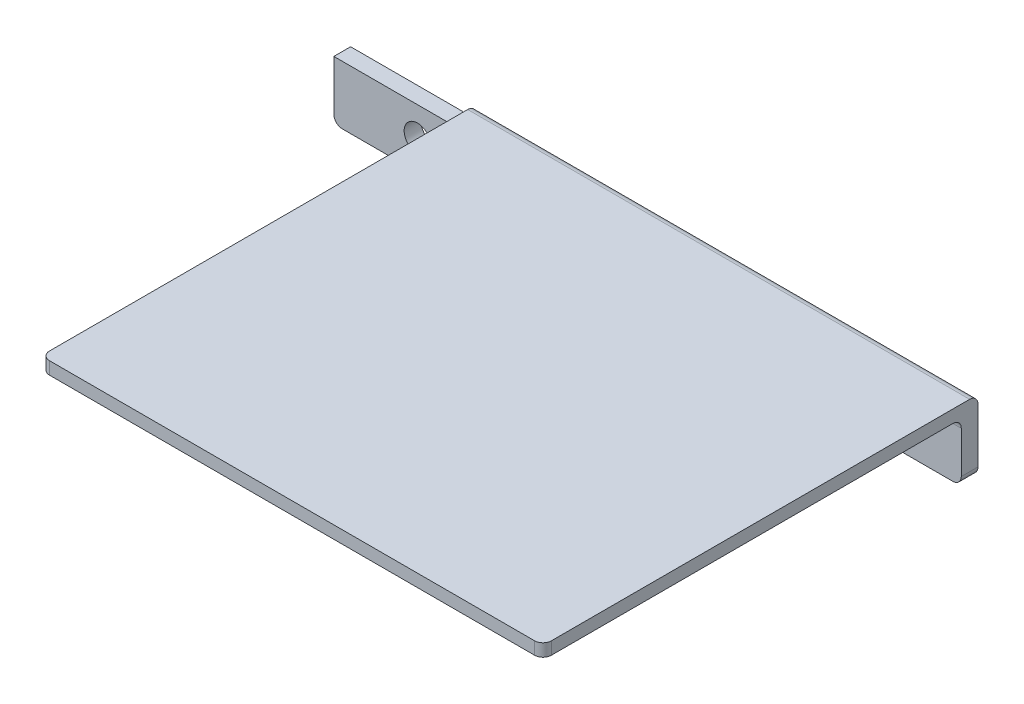
SolidWorks part; units mm, degrees
ref_plane "前视基准面" through (0, 0, 0) normal (0, 0, 1) x (1, 0, 0)
ref_plane "上视基准面" through (0, 0, 0) normal (0, 1, 0) x (1, 0, 0)
ref_plane "右视基准面" through (0, 0, 0) normal (1, 0, 0) x (0, 0, -1)
sketch "草图1" plane through (0, 0, 0) normal (0, 0, 1) x (1, 0, 0)
  line L1 (15, 0) -> (75, 0)
  line L2 (0, -1.5) -> (0, -8.5)
  line L3 (0, -8.5) -> (75, -8.5)
  line L4 (75, 0) -> (75, -8.5)
  line L7 (0, -1.5) -> (15, -1.5)
  line L8 (15, 0) -> (15, -1.5)
  circle A0 centre (10, -5) radius 1.6
  circle A1 centre (60, -5) radius 1.6
  dimension "D3" = 2
  dimension "D4" = 10
  dimension "D5" = 3.5
  dimension "D1" = 8.5
  dimension "D6" = 15
  dimension "D7" = 1.5
extrude "凸台-拉伸1" add sketch "草图1" along normal blind 2
sketch "草图2" plane through (0, 0, 2) normal (0, 0, 1) x (1, 0, 0)
  line L0 (75, -8.5) -> (75, 0) construction
  line L1 (15, 0) -> (75, 0)
  line L2 (15, 0) -> (15, -1.5)
  line L3 (15, -1.5) -> (75, -1.5)
  line L4 (75, 0) -> (75, -1.5)
  dimension "D1" = 1.5
  dimension "D2" = 60
extrude "凸台-拉伸2" add sketch "草图2" along normal blind 50
fillet "圆角1" radius 1 6 edges at (45, 0, 0) (75, -0.75, 52) (15, -0.75, 52) (75, -8.5, 1) (0, -8.5, 1) (45, -1.5, 2)
